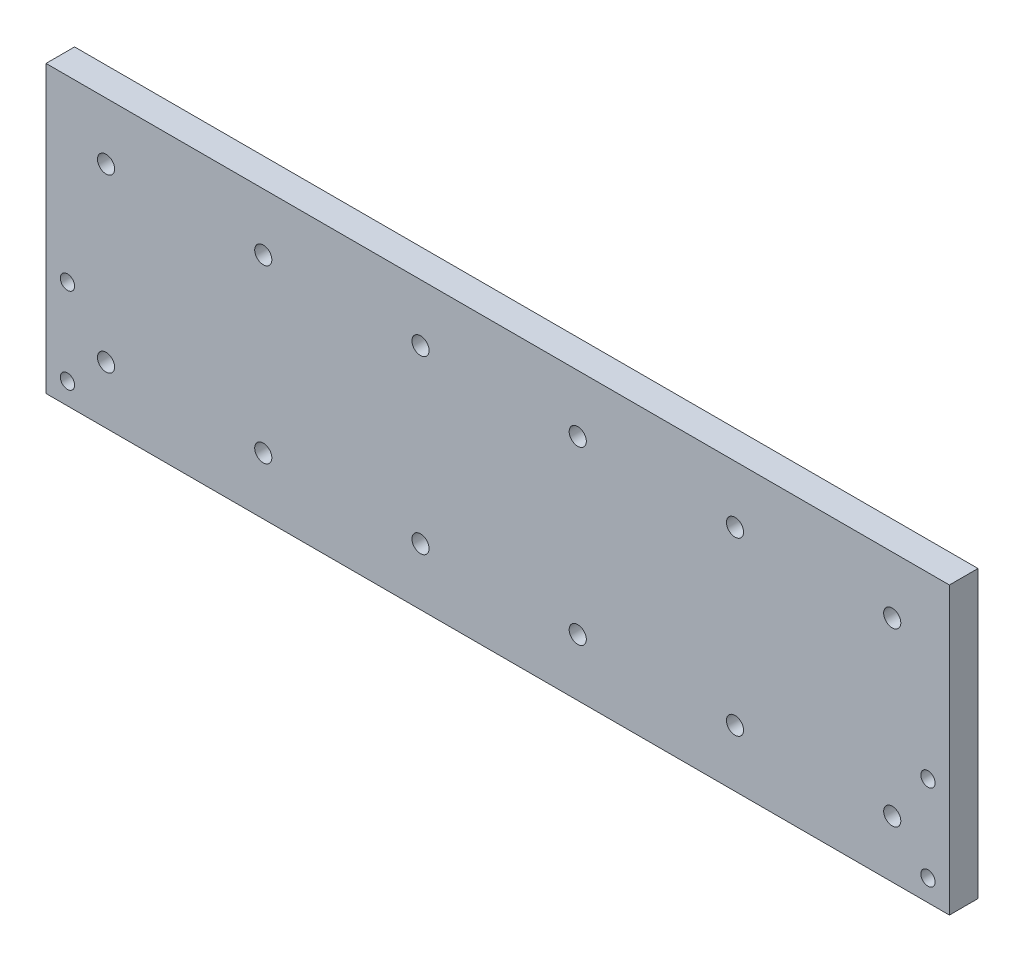
SolidWorks part; units mm, degrees
ref_plane "Front Plane" through (0, 0, 0) normal (0, 0, 1) x (1, 0, 0)
ref_plane "Top Plane" through (0, 0, 0) normal (0, 1, 0) x (1, 0, 0)
ref_plane "Right Plane" through (0, 0, 0) normal (1, 0, 0) x (0, 0, -1)
sketch "Sketch1" plane through (0, 0, 0) normal (0, 0, 1) x (1, 0, 0)
  line L1 (-158, -50) -> (158, -50)
  line L2 (-158, -50) -> (-158, 50)
  line L3 (-158, 50) -> (158, 50)
  line L4 (158, -50) -> (158, 50)
  line L5 (-158, -50) -> (158, 50) construction
  line L6 (-158, 50) -> (158, -50) construction
  point P0 (0, 0)
  dimension "D1" = 100
  dimension "D2" = 316
extrude "Boss-Extrude1" add sketch "Sketch1" along normal blind 10
sketch "Sketch4" plane through (0, 0, 0) normal (0, 0, -1) x (-1, 0, 0)
  line L0 (-158, 0) -> (158, 0) construction
  line L1 (-158, -50) -> (-158, 50) construction
  line L2 (158, 50) -> (158, -50) construction
  line L3 (-149.828, 30) -> (106.7881, 30) construction
  circle A0 centre (-138, 30) radius 3
  circle A1 centre (-83, 30) radius 3
  circle A2 centre (-28, 30) radius 3
  circle A3 centre (27, 30) radius 3
  circle A4 centre (82, 30) radius 3
  circle A5 centre (137, 30) radius 3
  circle A6 centre (137, -30) radius 3
  circle A7 centre (82, -30) radius 3
  circle A8 centre (27, -30) radius 3
  circle A9 centre (-28, -30) radius 3
  circle A10 centre (-83, -30) radius 3
  circle A11 centre (-138, -30) radius 3
  dimension "D3" = 6
  dimension "D2" = 20
  dimension "D4" = 60
  dimension "D1" = 6
extrude "Cut-Extrude1" cut sketch "Sketch4" against normal up to next
sketch "Sketch5" plane through (0, 0, 10) normal (0, 0, 1) x (1, 0, 0)
  line L0 (-150.5, 50) -> (-150.5, -50) construction
  line L1 (158, 50) -> (-158, 50) construction
  line L2 (-158, -50) -> (158, -50) construction
  line L3 (150.5, 50) -> (150.5, -50) construction
  line L4 (-158, 50) -> (-158, -50) construction
  line L5 (158, -50) -> (158, 50) construction
  circle A0 centre (-150.5, -42.5) radius 2.5
  circle A1 centre (150.5, -42.5) radius 2.5
  circle A2 centre (-150.5, -12.5) radius 2.5
  circle A3 centre (150.5, -12.5) radius 2.5
  dimension "D3" = 5
  dimension "D5" = 7.5
  dimension "D6" = 5
  dimension "D7" = 30
  dimension "D9" = 5
  dimension "D10" = 5
  dimension "D1" = 7.5
  dimension "D2" = 7.5
  dimension "D4" = 7.5
  dimension "D8" = 30
extrude "Cut-Extrude2" cut sketch "Sketch5" against normal up to next
sketch "Sketch6" plane through (0, 0, 0) normal (0, 0, -1) x (-1, 0, 0)
  circle A0 centre (-150.5, -42.5) radius 4.5
  circle A1 centre (-150.5, -12.5) radius 4.5
  circle A2 centre (150.5, -12.5) radius 4.5
  circle A3 centre (150.5, -42.5) radius 4.5
  dimension "D1" = 9
  dimension "D2" = 9
  dimension "D3" = 9
  dimension "D4" = 9
extrude "Cut-Extrude3" cut sketch "Sketch6" against normal blind 5
